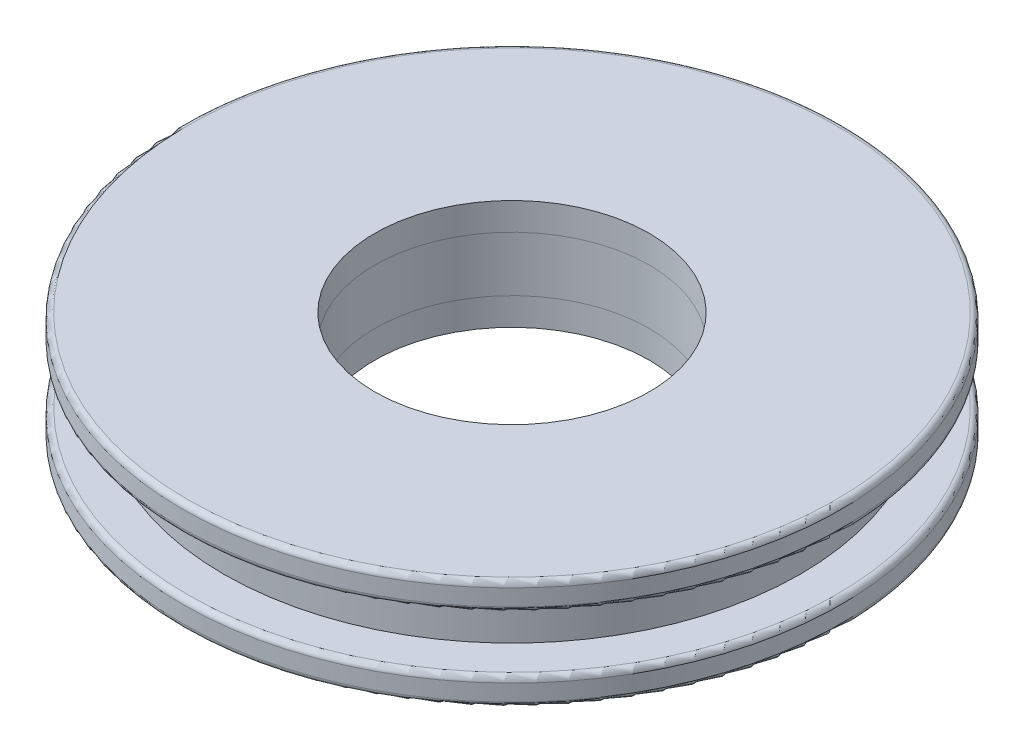
SolidWorks part; units mm, degrees
ref_plane "前视基准面" through (0, 0, 0) normal (0, 0, 1) x (1, 0, 0)
ref_plane "上视基准面" through (0, 0, 0) normal (0, 1, 0) x (1, 0, 0)
ref_plane "右视基准面" through (0, 0, 0) normal (1, 0, 0) x (0, 0, -1)
sketch "草图1" plane through (0, 0, 0) normal (0, 1, 0) x (1, 0, 0)
  circle A0 centre (0, 0) radius 5
  circle A1 centre (0, 0) radius 12
  dimension "D1" = 10
  dimension "D2" = 24
extrude "凸台-拉伸1" add sketch "草图1" along normal blind 1
sketch "草图3" plane through (0, 1, 0) normal (0, 1, 0) x (1, 0, 0)
  circle A0 centre (0, 0) radius 5
  circle A1 centre (0, 0) radius 12
extrude "凸台-拉伸2" add sketch "草图3" along normal blind 2 separate body
sketch "草图4" plane through (0, 3, 0) normal (0, 1, 0) x (1, 0, 0)
  circle A0 centre (0, 0) radius 5
  circle A1 centre (0, 0) radius 12
extrude "凸台-拉伸3" add sketch "草图4" along normal blind 1 separate body
sketch "草图5" plane through (0, 0, 0) normal (1, 0, 0) x (0, 0, -1)
  line L0 (12, 1) -> (12, 3) construction
  line L1 (10.5, 1) -> (13.5, 1)
  line L2 (10.5, 1) -> (10.5, 3)
  line L3 (10.5, 3) -> (13.5, 3)
  line L4 (13.5, 1) -> (13.5, 3)
  line L5 (10.5, 1) -> (13.5, 3) construction
  line L6 (10.5, 3) -> (13.5, 1) construction
  point P0 (12, 2)
ref_axis "基准轴1" through (0, 3, 0) along (0, -1, 0)
revolve "切除-旋转1" cut sketch "草图5" angle 360 about axis through (0, 3, 0) along (0, -1, 0)
fillet "圆角1" radius 0.2 1 edges at (0, 4, 12)
fillet "圆角2" radius 0.2 1 edges at (0, 3, 12)
fillet "圆角3" radius 0.2 1 edges at (0, 1, 12)
fillet "圆角4" radius 0.2 1 edges at (0, 0, 12)
